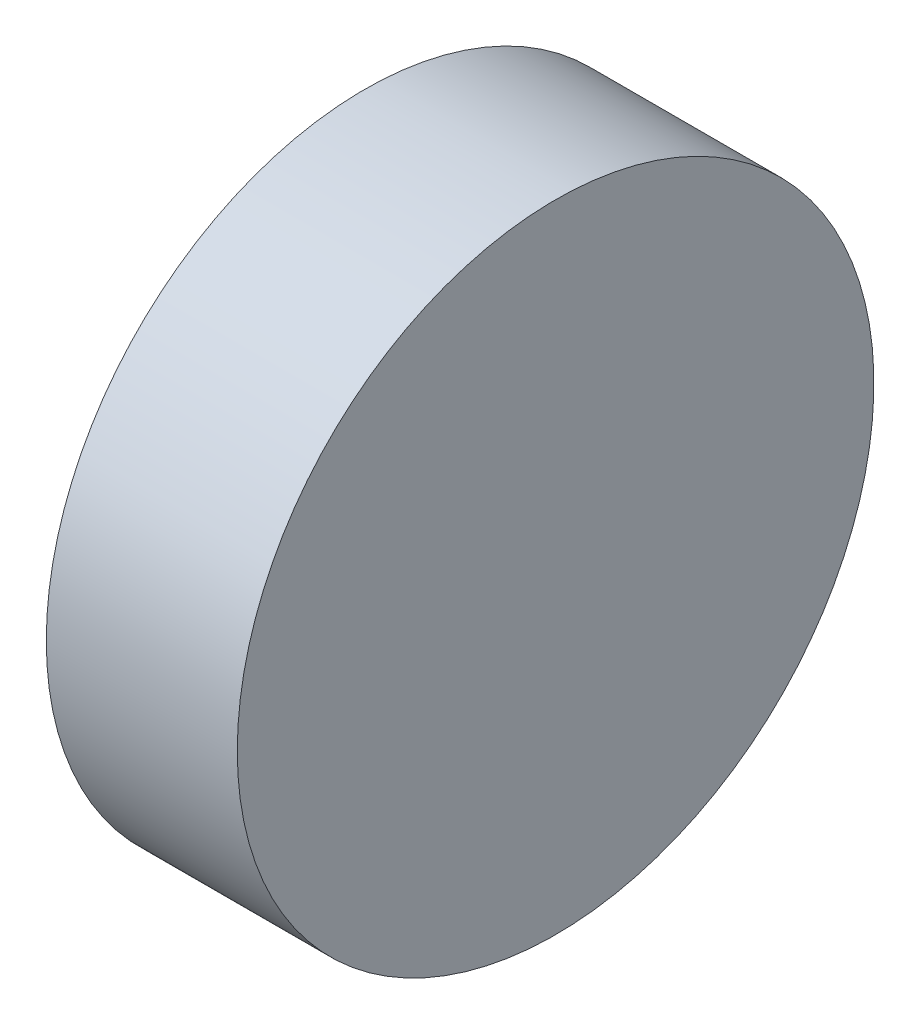
SolidWorks part; units mm, degrees
ref_plane "Front Plane" through (0, 0, 0) normal (0, 0, 1) x (1, 0, 0)
ref_plane "Top Plane" through (0, 0, 0) normal (0, 1, 0) x (1, 0, 0)
ref_plane "Right Plane" through (0, 0, 0) normal (1, 0, 0) x (0, 0, -1)
sketch "Sketch1" plane through (0, 0, 0) normal (1, 0, 0) x (0, 0, -1)
  circle A0 centre (0, 0) radius 25.4
  dimension "D1" = 50.8
extrude "Boss-Extrude1" add sketch "Sketch1" along normal blind 15.24 contours A0
